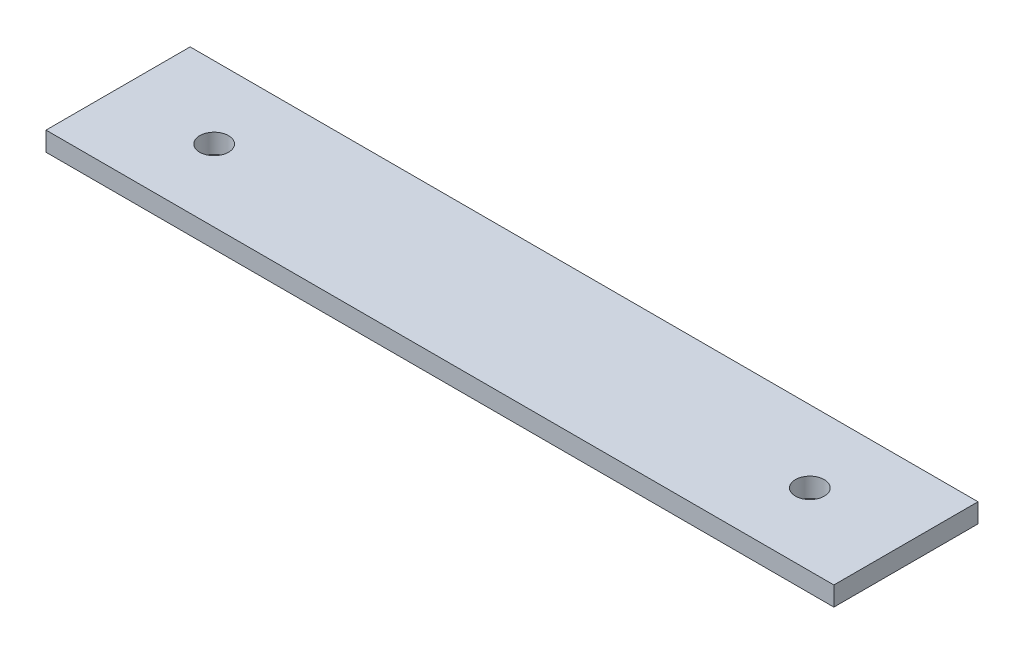
SolidWorks part; units mm, degrees
ref_plane "Front Plane" through (0, 0, 0) normal (0, 0, 1) x (1, 0, 0)
ref_plane "Top Plane" through (0, 0, 0) normal (0, 1, 0) x (1, 0, 0)
ref_plane "Right Plane" through (0, 0, 0) normal (1, 0, 0) x (0, 0, -1)
sketch "Sketch1" plane through (0, 0, 0) normal (0, 1, 0) x (1, 0, 0)
  line L1 (0, 0) -> (82, 0)
  line L2 (0, 0) -> (0, 15)
  line L3 (0, 15) -> (82, 15)
  line L4 (82, 0) -> (82, 15)
  circle A0 centre (10, 7.5) radius 1.5
  circle A1 centre (72, 7.5) radius 1.5
  dimension "D3" = 7.5
  dimension "D4" = 10
  dimension "D5" = 10
  dimension "D6" = 7.5
  dimension "D1" = 82
  dimension "D2" = 15
extrude "Boss-Extrude1" add sketch "Sketch1" along normal blind 2
